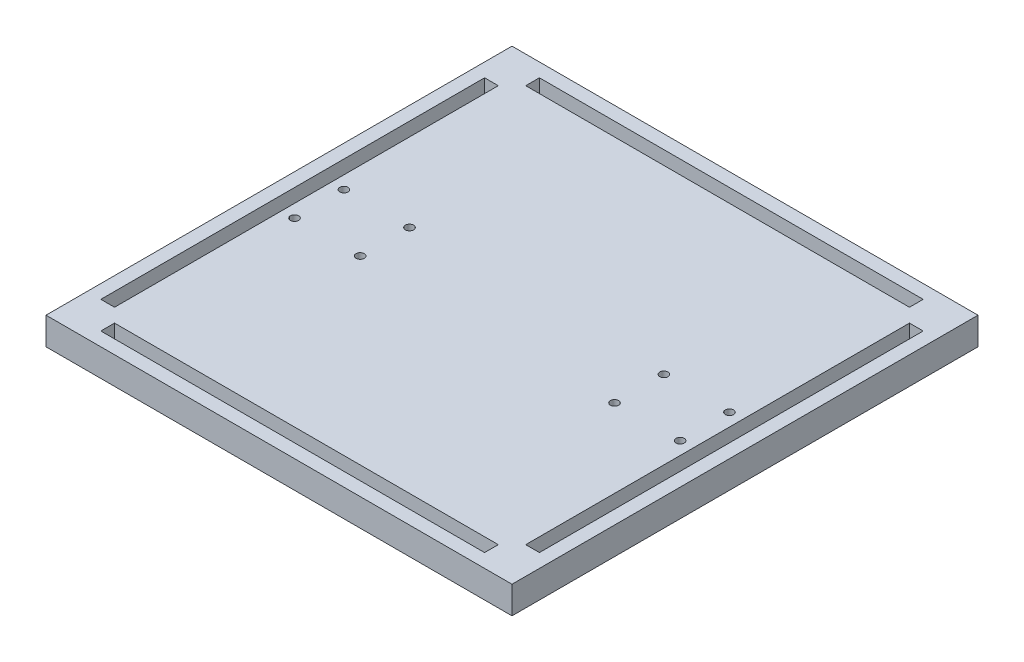
SolidWorks part; units mm, degrees
ref_plane "Front Plane" through (0, 0, 0) normal (0, 0, 1) x (1, 0, 0)
ref_plane "Top Plane" through (0, 0, 0) normal (0, 1, 0) x (1, 0, 0)
ref_plane "Right Plane" through (0, 0, 0) normal (1, 0, 0) x (0, 0, -1)
sketch "Sketch2" plane through (0, 0, 0) normal (0, 1, 0) x (1, 0, 0)
  line L1 (-85, -85) -> (85, -85)
  line L2 (-85, -85) -> (-85, 85)
  line L3 (-85, 85) -> (85, 85)
  line L4 (85, -85) -> (85, 85)
  line L5 (-85, -85) -> (85, 85) construction
  line L6 (-85, 85) -> (85, -85) construction
  point P0 (0, 0)
  dimension "D1" = 170
  dimension "D2" = 170
extrude "Boss-Extrude1" add sketch "Sketch2" along normal blind 10
sketch "Sketch3" plane through (0, 10, 0) normal (0, 1, 0) x (1, 0, 0)
  line L14 (-55, 0) -> (55, 0) construction
  line L20 (0, -55) -> (0, 55) construction
  line L29 (-80, 70) -> (-80, -70)
  line L30 (-70, -80) -> (70, -80)
  line L31 (80, -70) -> (80, 70)
  line L32 (70, 80) -> (-70, 80)
  line L33 (-80, -70) -> (-75, -70)
  line L34 (-70, -80) -> (-70, -75.0019)
  line L35 (-80, 70) -> (-75, 70)
  line L36 (-70, 80) -> (-70, 75)
  line L37 (70, 80) -> (70, 75)
  line L38 (80, 70) -> (75, 70)
  line L39 (80, -70) -> (75, -70)
  line L40 (70, -80) -> (70, -75.0019)
  line L41 (-70, -75.0019) -> (70, -75.0019)
  line L42 (-75, 70) -> (-75, -70)
  line L43 (-70, 75) -> (70, 75)
  line L44 (75, 70) -> (75, -70)
extrude "Cut-Extrude1" cut sketch "Sketch3" against normal blind 10
sketch "Sketch4" plane through (0, 0, 0) normal (0, -1, 0) x (-1, 0, 0)
  circle A0 centre (-70.33, -9) radius 1.5
  circle A1 centre (-70.33, 9) radius 1.5
  circle A2 centre (70.33, 9) radius 1.5
  circle A3 centre (70.33, -9) radius 1.5
  circle A4 centre (46.4, 9) radius 1.5
  circle A5 centre (46.4, -9) radius 1.5
  circle A6 centre (-46.4, -9) radius 1.5
  circle A7 centre (-46.4, 9) radius 1.5
extrude "Cut-Extrude2" cut sketch "Sketch4" along normal through all and the other way through all
